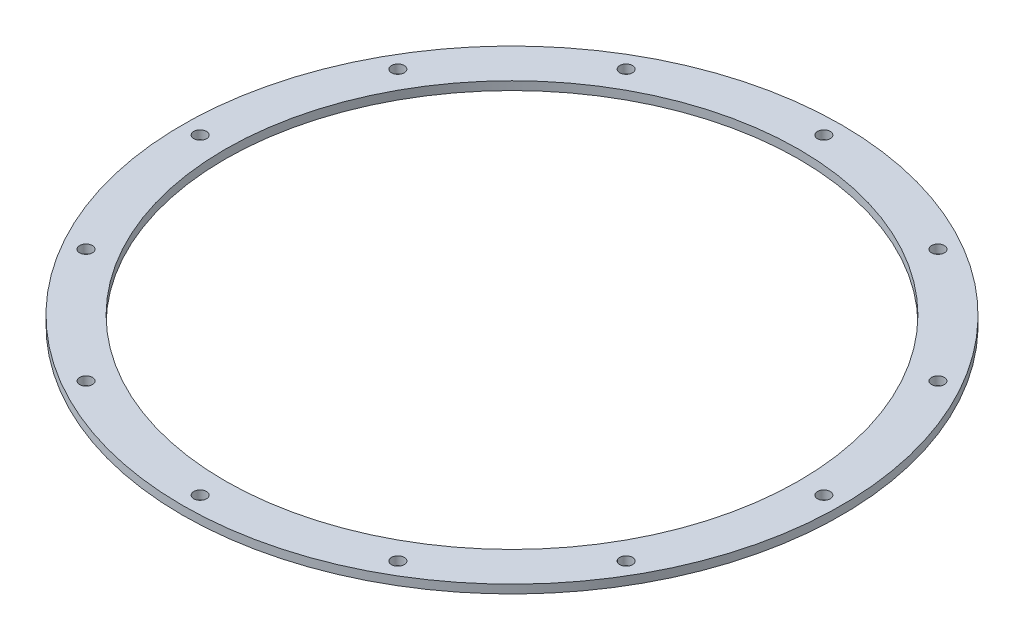
SolidWorks part; units mm, degrees
material "ASTM A36 Steel"
ref_plane "Front Plane" through (0, 0, 0) normal (0, 0, 1) x (1, 0, 0)
ref_plane "Top Plane" through (0, 0, 0) normal (0, 1, 0) x (1, 0, 0)
ref_plane "Right Plane" through (0, 0, 0) normal (1, 0, 0) x (0, 0, -1)
sketch "Sketch1" plane through (0, 0, 0) normal (0, 1, 0) x (1, 0, 0)
  circle A0 centre (0, 0) radius 202.5
  circle A1 centre (0, 0) radius 232.5
  dimension "D1" = 405
  dimension "D2" = 465
extrude "Boss-Extrude1" add sketch "Sketch1" along normal blind 6
sketch "Sketch2" plane through (0, 6, 0) normal (0, 1, 0) x (1, 0, 0)
  circle A0 centre (0, 0) radius 220 construction
  circle A1 centre (0, 220) radius 4.5
  dimension "D1" = 440
  dimension "D2" = 9
extrude "Cut-Extrude1" cut sketch "Sketch2" against normal blind 10
pattern_circular "CirPattern1" count 12 every 30 about axis through (0, 0, 0) along (0, 1, 0) of "Cut-Extrude1"
